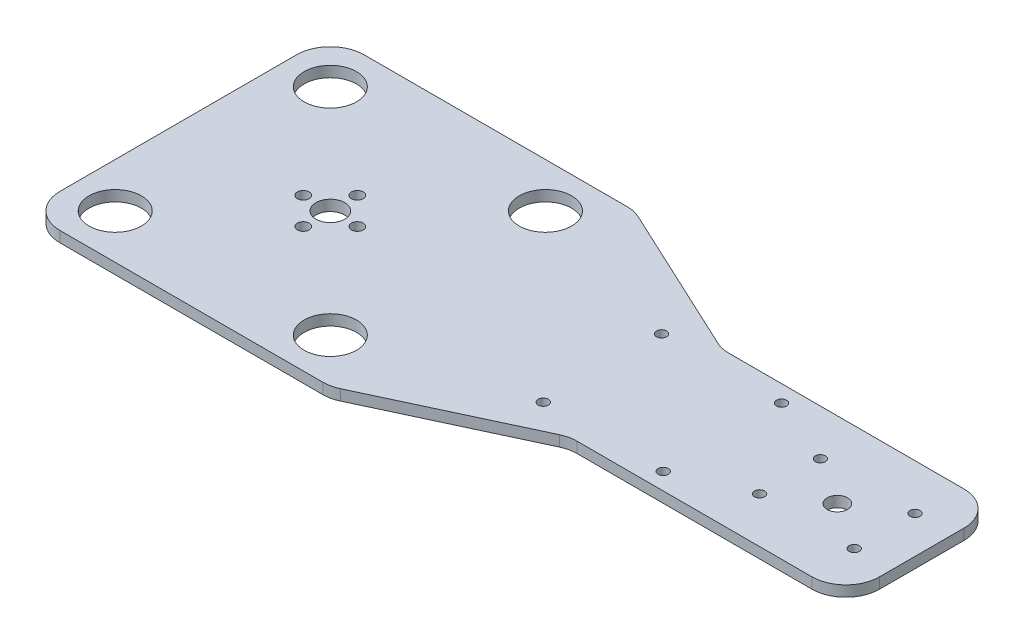
SolidWorks part; units mm, degrees
ref_plane "Front Plane" through (0, 0, 0) normal (0, 0, 1) x (1, 0, 0)
ref_plane "Top Plane" through (0, 0, 0) normal (0, 1, 0) x (1, 0, 0)
ref_plane "Right Plane" through (0, 0, 0) normal (1, 0, 0) x (0, 0, -1)
sketch "Sketch1" plane through (0, 0, 0) normal (0, 1, 0) x (1, 0, 0)
  line L0 (45, -45) -> (93.2514, -22.5)
  line L1 (-25, 22.5) -> (45, 22.5) construction
  line L2 (-25, 22.5) -> (-25, -22.5) construction
  line L3 (-25, -22.5) -> (45, -22.5) construction
  line L4 (175, 22.5) -> (175, -22.5)
  line L5 (-45, -45) -> (45, -45)
  line L6 (-45, -45) -> (-45, 45)
  line L7 (-45, 45) -> (45, 45)
  line L8 (45, -45) -> (45, 45) construction
  line L9 (-45, -45) -> (45, 45) construction
  line L10 (-45, 45) -> (45, -45) construction
  line L11 (-45, 0) -> (45, 0) construction
  line L12 (45, 45) -> (93.2514, 22.5)
  line L13 (93.2514, -22.5) -> (175, -22.5)
  line L14 (93.2514, 22.5) -> (175, 22.5)
  point P4 (-25, 0)
  point P6 (0, 0)
  dimension "D1" = 45
  dimension "D2" = 200
  dimension "D3" = 25
  dimension "D4" = 90
  dimension "D5" = 65
extrude "Boss-Extrude1" add sketch "Sketch1" along normal blind 3.175
sketch "Sketch4" plane through (0, 3.175, 0) normal (0, 1, 0) x (1, 0, 0)
  line L0 (175, 0) -> (-45, 0) construction
  line L1 (175, -22.5) -> (175, 22.5) construction
  line L3 (150, 22.5) -> (150, -22.5) construction
  line L6 (-45, 45) -> (-45, -45) construction
  line L7 (175, 22.5) -> (93.2514, 22.5) construction
  line L8 (93.2514, -22.5) -> (175, -22.5) construction
  circle A0 centre (150, 0) radius 3
  circle A1 centre (136, 9) radius 1.5
  circle A2 centre (164, 9) radius 1.5
  circle A3 centre (164, -9) radius 1.5
  circle A4 centre (136, -9) radius 1.5
  dimension "D1" = 6
  dimension "D5" = 3
  dimension "D2" = 25
  dimension "D3" = 14
  dimension "D4" = 9
extrude "Cut-Extrude1" cut sketch "Sketch4" against normal through all
sketch "Sketch5" plane through (0, 3.175, 0) normal (0, 1, 0) x (1, 0, 0)
  circle A0 centre (0, 0) radius 4.25
  dimension "D1" = 8.5
extrude "Cut-Extrude2" cut sketch "Sketch5" against normal through all
sketch "Sketch10" plane through (0, 3.175, 0) normal (0, 1, 0) x (1, 0, 0)
  line L0 (-45, 0) -> (175, 0) construction
  line L2 (175, -22.5) -> (175, 22.5) construction
  line L4 (93.2514, -22.5) -> (175, -22.5) construction
  line L5 (-45, 45) -> (-45, -45) construction
  circle A0 centre (80.5, -17.5) radius 1.5
  circle A1 centre (0, 0) radius 4.25 construction
  circle A2 centre (116, -17.5) radius 1.5
  circle A3 centre (136, -9) radius 1.5 construction
  circle A4 centre (116, 17.5) radius 1.5
  circle A5 centre (80.5, 17.5) radius 1.5
  dimension "D3" = 3
  dimension "D4" = 20
  dimension "D1" = 80.5
  dimension "D2" = 5
extrude "Cut-Extrude4" cut sketch "Sketch10" against normal through all
fillet "Fillet1" radius 10 4 edges at (175, 1.5875, -22.5) (175, 1.5875, 22.5) (-45, 1.5875, -45) (-45, 1.5875, 45)
fillet "Fillet2" radius 10 4 edges at (45, 1.5875, -45) (93.2514, 1.5875, -22.5) (93.2514, 1.5875, 22.5) (45, 1.5875, 45)
sketch "Sketch11" plane through (0, 3.175, 0) normal (0, 1, 0) x (1, 0, 0)
  line L0 (0, 45) -> (0, -45) construction
  line L1 (42.7831, 45) -> (-35, 45) construction
  line L2 (-35, -45) -> (42.7831, -45) construction
  line L3 (31.8198, -31.8198) -> (0, 0) construction
  line L5 (0, 0) -> (-31.8198, 31.8198) construction
  circle A0 centre (-31.8198, 31.8198) radius 7.75
  circle A1 centre (31.8198, 31.8198) radius 7.75
  circle A2 centre (31.8198, -31.8198) radius 7.75
  circle A3 centre (-31.8198, -31.8198) radius 7.75
  dimension "D1" = 15.5
  dimension "D2" = 45
  dimension "D3" = 45
  dimension "D4" = 4
extrude "Cut-Extrude5" cut sketch "Sketch11" against normal through all
sketch "Sketch13" plane through (0, 3.175, 0) normal (0, 1, 0) x (1, 0, 0)
  line L0 (0, 0) -> (8, 0) construction
  line L1 (0, 0) -> (-8, 0) construction
  circle A0 centre (8, 0) radius 1.75
  circle A2 centre (0, 0) radius 4.25 construction
  circle A3 centre (0, -8) radius 1.75
  circle A4 centre (-8, 0) radius 1.75
  circle A5 centre (0, 8) radius 1.75
  dimension "D1" = 3.5
  dimension "D2" = 8
  dimension "D3" = 4
extrude "Cut-Extrude6" cut sketch "Sketch13" against normal through all
